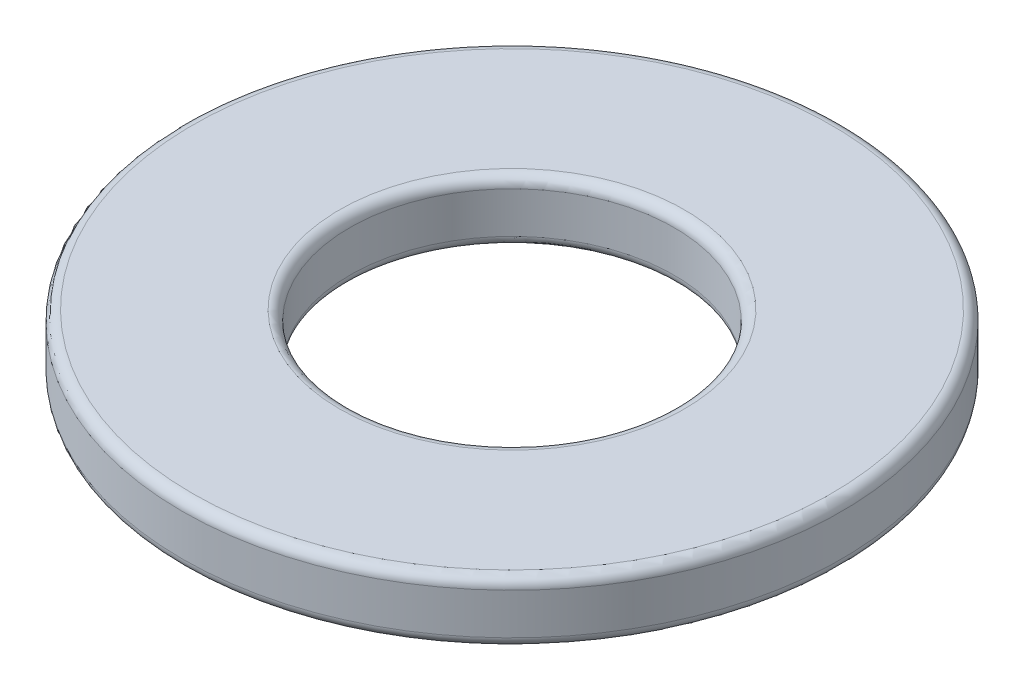
SolidWorks part; units mm, degrees
material "NdFeB"
ref_plane "Front Plane" through (0, 0, 0) normal (0, 0, 1) x (1, 0, 0)
ref_plane "Top Plane" through (0, 0, 0) normal (0, 1, 0) x (1, 0, 0)
ref_plane "Right Plane" through (0, 0, 0) normal (1, 0, 0) x (0, 0, -1)
sketch "Sketch2" plane through (0, 0, 0) normal (0, 1, 0) x (1, 0, 0)
  circle A0 centre (0, 0) radius 16
  circle A1 centre (0, 0) radius 7.875
  dimension "D1" = 32
  dimension "D2" = 15.75
extrude "Boss-Extrude1" add sketch "Sketch2" along normal mid plane 3
fillet "Fillet1" radius 0.5 4 edges at (0, -1.5, 7.875) (0, -1.5, 16) (0, 1.5, 7.875) (0, 1.5, 16)
